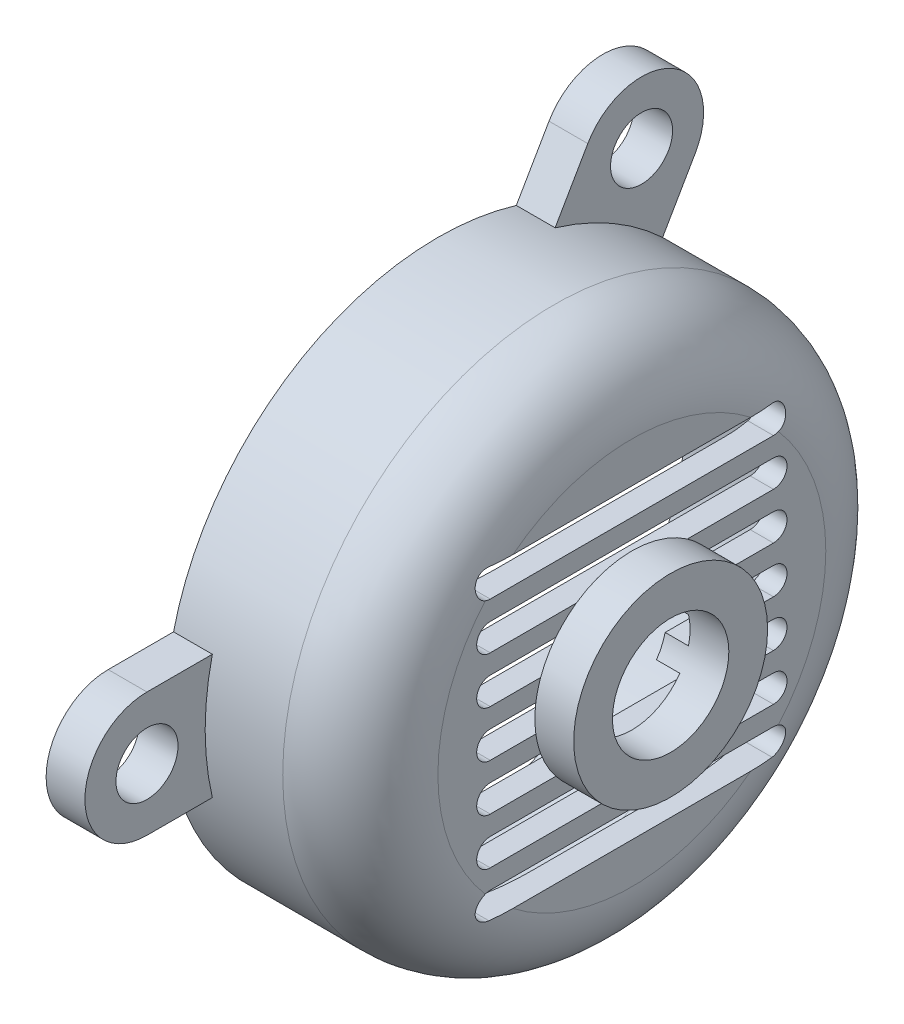
SolidWorks part; units mm, degrees
ref_plane "Front Plane" through (0, 0, 0) normal (1, 0, 0) x (0, 1, 0)
ref_plane "Top Plane" through (0, 0, 0) normal (0, 0, 1) x (0, 1, 0)
ref_plane "Right Plane" through (0, 0, 0) normal (0, 1, 0) x (-1, 0, 0)
sketch "Sketch2" plane through (0, 0, 0) normal (0, 1, 0) x (-1, 0, 0)
  line L0 (0, 0) -> (31206.1457, 0) construction
  line L1 (0, 0) -> (0, 31206.1457) construction
  line L2 (0, 32) -> (-12, 32)
  line L3 (-22, 22) -> (-22, 7.5)
  line L4 (0, 32) -> (0, 35)
  line L5 (-22, 12.5) -> (-30, 12.5)
  line L6 (-30, 12.5) -> (-30, 7.5)
  line L7 (0, 35) -> (-15, 35)
  line L8 (-25, 25) -> (-25, 12.5)
  line L12 (-22, 7.5) -> (-22, 12.5)
  line L13 (-30, 7.5) -> (-22, 7.5)
  arc A0 (-12, 32) -> (-22, 22) centre (-12, 22) ccw
  arc A1 (-15, 35) -> (-25, 25) centre (-15, 25) ccw
  point P9 (-6, 32)
  dimension "D8" = 10
  dimension "D1" = 70
  dimension "D2" = 64
  dimension "D3" = 25
  dimension "D4" = 3
  dimension "D5" = 5
  dimension "D6" = 25
  dimension "D7" = 30
revolve "Revolve1" add sketch "Sketch2" angle 360 about L0
sketch "Sketch3" plane through (0, 0, 0) normal (1, 0, 0) x (0, 1, 0)
  line L0 (8, 42.5) -> (8, 34.0735)
  line L1 (-8, 42.5) -> (-8, 34.0735)
  circle A0 centre (0, 42.5) radius 4
  arc A1 (8, 42.5) -> (-8, 42.5) centre (0, 42.5) ccw
  circle A2 centre (0, 0) radius 35 construction
  arc A3 (8, 34.0735) -> (-8.1547, 34.0368) centre (0, 0) ccw
  dimension "D1" = 16
  dimension "D2" = 8
  dimension "D3" = 42.5
extrude "Boss-Extrude1" add sketch "Sketch3" along normal blind 5 contours A3 L0 A1 L1 A0
pattern_circular "CirPattern1" count 3 over 360 about axis through (0, 0, 0) along (1, 0, 0) of "Boss-Extrude1"
sketch "Sketch4" plane through (25, 0, 0) normal (1, 0, 0) x (0, 1, 0)
  line L0 (0, 18.25) -> (0, -18.25) construction
  line L1 (1.75, 18.25) -> (1.75, -18.25)
  line L2 (-1.75, 18.25) -> (-1.75, -18.25)
  line L3 (-41.1096, 0) -> (47.9474, 0) construction
  line L4 (6, 18.25) -> (6, -18.25) construction
  line L5 (7.75, 18.25) -> (7.75, -18.25)
  line L6 (4.25, 18.25) -> (4.25, -18.25)
  line L7 (12, 18.25) -> (12, -18.25) construction
  line L8 (13.75, 18.25) -> (13.75, -18.25)
  line L9 (10.25, 18.25) -> (10.25, -18.25)
  line L10 (18, 18.25) -> (18, -18.25) construction
  line L11 (19.75, 18.25) -> (19.75, -18.25)
  line L12 (16.25, 18.25) -> (16.25, -18.25)
  line L13 (-6, 18.25) -> (-6, -18.25) construction
  line L14 (-4.25, 18.25) -> (-4.25, -18.25)
  line L15 (-7.75, 18.25) -> (-7.75, -18.25)
  line L16 (-12, 18.25) -> (-12, -18.25) construction
  line L17 (-10.25, 18.25) -> (-10.25, -18.25)
  line L18 (-13.75, 18.25) -> (-13.75, -18.25)
  line L19 (-18, 18.25) -> (-18, -18.25) construction
  line L20 (-16.25, 18.25) -> (-16.25, -18.25)
  line L21 (-19.75, 18.25) -> (-19.75, -18.25)
  arc A0 (1.75, 18.25) -> (-1.75, 18.25) centre (0, 18.25) ccw
  arc A1 (-1.75, -18.25) -> (1.75, -18.25) centre (0, -18.25) ccw
  arc A2 (7.75, 18.25) -> (4.25, 18.25) centre (6, 18.25) ccw
  arc A3 (4.25, -18.25) -> (7.75, -18.25) centre (6, -18.25) ccw
  arc A4 (13.75, 18.25) -> (10.25, 18.25) centre (12, 18.25) ccw
  arc A5 (10.25, -18.25) -> (13.75, -18.25) centre (12, -18.25) ccw
  arc A6 (19.75, 18.25) -> (16.25, 18.25) centre (18, 18.25) ccw
  arc A7 (16.25, -18.25) -> (19.75, -18.25) centre (18, -18.25) ccw
  arc A8 (-4.25, 18.25) -> (-7.75, 18.25) centre (-6, 18.25) ccw
  arc A9 (-7.75, -18.25) -> (-4.25, -18.25) centre (-6, -18.25) ccw
  arc A10 (-10.25, 18.25) -> (-13.75, 18.25) centre (-12, 18.25) ccw
  arc A11 (-13.75, -18.25) -> (-10.25, -18.25) centre (-12, -18.25) ccw
  arc A12 (-16.25, 18.25) -> (-19.75, 18.25) centre (-18, 18.25) ccw
  arc A13 (-19.75, -18.25) -> (-16.25, -18.25) centre (-18, -18.25) ccw
  point P2 (0, 0)
  point P13 (6, 0)
  point P20 (12, 0)
  point P27 (18, 0)
  point P34 (-6, 0)
  point P41 (-12, 0)
  point P48 (-18, 0)
  dimension "D1" = 1.75
  dimension "D2" = 36.5
  dimension "D3" = 4
  dimension "D4" = 4
extrude "Cut-Extrude1" cut sketch "Sketch4" against normal blind 5
